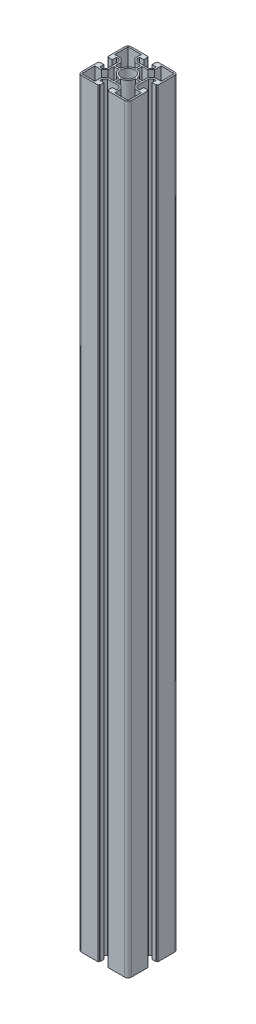
SolidWorks part; units mm, degrees
ref_plane "前视基准面" through (0, 0, 0) normal (0, 0, 1) x (1, 0, 0)
ref_plane "上视基准面" through (0, 0, 0) normal (0, 1, 0) x (1, 0, 0)
ref_plane "右视基准面" through (0, 0, 0) normal (1, 0, 0) x (0, 0, -1)
sketch "草图1" plane through (0, 0, 0) normal (0, 1, 0) x (1, 0, 0)
  line L0 (0, 32.6515) -> (0, -47.5) construction
  line L2 (-54.5455, 0) -> (57.7273, 0) construction
  line L82 (-16, 1) -> (-9.9499, 1)
  line L83 (-30, 6) -> (-28.5, 6)
  line L88 (-16, 1) -> (-16, 7.8284)
  line L89 (-16, 7.8284) -> (-20.1716, 12)
  line L90 (-20.1716, 12) -> (-28, 12)
  line L91 (-28, 12) -> (-28, 28)
  line L92 (-28, 28) -> (-12, 28)
  line L93 (-12, 28) -> (-12, 20.1716)
  line L94 (-12, 20.1716) -> (-7.8284, 16)
  line L95 (-7.8284, 16) -> (-1, 16)
  line L96 (-1, 16) -> (-1, 9.9499)
  line L97 (1, 9.9499) -> (1, 16)
  line L98 (1, 16) -> (7.8284, 16)
  line L99 (7.8284, 16) -> (12, 20.1716)
  line L100 (12, 20.1716) -> (12, 28)
  line L101 (12, 28) -> (28, 28)
  line L102 (28, 28) -> (28, 12)
  line L103 (28, 12) -> (20.1716, 12)
  line L104 (20.1716, 12) -> (16, 7.8284)
  line L105 (16, 7.8284) -> (16, 1)
  line L106 (16, 1) -> (9.9499, 1)
  line L107 (9.9499, -1) -> (16, -1)
  line L108 (16, -1) -> (16, -7.8284)
  line L109 (16, -7.8284) -> (20.1716, -12)
  line L110 (20.1716, -12) -> (28, -12)
  line L111 (28, -12) -> (28, -28)
  line L112 (28, -28) -> (12, -28)
  line L113 (12, -28) -> (12, -20.1716)
  line L114 (12, -20.1716) -> (7.8284, -16)
  line L115 (7.8284, -16) -> (1, -16)
  line L116 (1, -16) -> (1, -9.9499)
  line L117 (-1, -9.9499) -> (-1, -16)
  line L118 (-1, -16) -> (-7.8284, -16)
  line L119 (-7.8284, -16) -> (-12, -20.1716)
  line L120 (-12, -20.1716) -> (-12, -28)
  line L121 (-12, -28) -> (-28, -28)
  line L122 (-28, -28) -> (-28, -12)
  line L123 (-28, -12) -> (-20.1716, -12)
  line L124 (-20.1716, -12) -> (-16, -7.8284)
  line L125 (-16, -7.8284) -> (-16, -1)
  line L126 (-28.5, 6) -> (-28.5, 5)
  line L127 (-28.5, 5) -> (-24, 5)
  line L128 (-24, 5) -> (-24, 10)
  line L129 (-24, 10) -> (-21, 10)
  line L130 (-21, 10) -> (-18, 7)
  line L131 (-18, 7) -> (-18, -7)
  line L132 (-18, -7) -> (-21, -10)
  line L133 (-21, -10) -> (-24, -10)
  line L134 (-24, -10) -> (-24, -5)
  line L135 (-24, -5) -> (-28.5, -5)
  line L136 (-28.5, -5) -> (-28.5, -6)
  line L137 (-28.5, -6) -> (-30, -6)
  line L138 (-30, -6) -> (-30, -26)
  line L139 (-26, -30) -> (-6, -30)
  line L140 (-6, -30) -> (-6, -28.5)
  line L141 (-6, -28.5) -> (-5, -28.5)
  line L142 (-5, -28.5) -> (-5, -24)
  line L143 (-5, -24) -> (-10, -24)
  line L144 (-10, -24) -> (-10, -21)
  line L145 (-10, -21) -> (-7, -18)
  line L146 (-7, -18) -> (7, -18)
  line L147 (7, -18) -> (10, -21)
  line L148 (10, -21) -> (10, -24)
  line L149 (10, -24) -> (5, -24)
  line L150 (5, -24) -> (5, -28.5)
  line L151 (5, -28.5) -> (6, -28.5)
  line L152 (6, -28.5) -> (6, -30)
  line L153 (6, -30) -> (26, -30)
  line L154 (30, -26) -> (30, -6)
  line L155 (30, -6) -> (28.5, -6)
  line L156 (28.5, -6) -> (28.5, -5)
  line L157 (28.5, -5) -> (24, -5)
  line L158 (24, -5) -> (24, -10)
  line L159 (24, -10) -> (21, -10)
  line L160 (21, -10) -> (18, -7)
  line L161 (18, -7) -> (18, 7)
  line L162 (18, 7) -> (21, 10)
  line L163 (21, 10) -> (24, 10)
  line L164 (24, 10) -> (24, 5)
  line L165 (24, 5) -> (28.5, 5)
  line L166 (28.5, 5) -> (28.5, 6)
  line L167 (28.5, 6) -> (30, 6)
  line L168 (30, 6) -> (30, 26)
  line L169 (26, 30) -> (6, 30)
  line L170 (6, 30) -> (6, 28.5)
  line L171 (6, 28.5) -> (5, 28.5)
  line L172 (5, 28.5) -> (5, 24)
  line L173 (5, 24) -> (10, 24)
  line L174 (10, 24) -> (10, 21)
  line L175 (10, 21) -> (7, 18)
  line L176 (7, 18) -> (-7, 18)
  line L177 (-7, 18) -> (-10, 21)
  line L178 (-10, 21) -> (-10, 24)
  line L179 (-10, 24) -> (-5, 24)
  line L180 (-5, 24) -> (-5, 28.5)
  line L181 (-5, 28.5) -> (-6, 28.5)
  line L182 (-6, 28.5) -> (-6, 30)
  line L183 (-6, 30) -> (-26, 30)
  line L184 (-30, 26) -> (-30, 6)
  line L185 (-16, -1) -> (-9.9499, -1)
  arc A41 (-9.9499, -1) -> (-1, -9.9499) centre (0, 0) ccw
  circle A42 centre (0, 0) radius 8
  arc A43 (-26, -30) -> (-30, -26) centre (-26, -26) cw
  arc A44 (26, 30) -> (30, 26) centre (26, 26) cw
  arc A45 (-26, 30) -> (-30, 26) centre (-26, 26) ccw
  arc A46 (26, -30) -> (30, -26) centre (26, -26) ccw
  arc A47 (9.9499, 1) -> (1, 9.9499) centre (0, 0) ccw
  arc A48 (-1, 9.9499) -> (-9.9499, 1) centre (0, 0) ccw
  arc A49 (1, -9.9499) -> (9.9499, -1) centre (0, 0) ccw
extrude "凸台-拉伸1" add sketch "草图1" along normal blind 915
ref_plane "基准面1" through (0, 750, 0) normal (0, -1, 0) x (-1, 0, 0)
